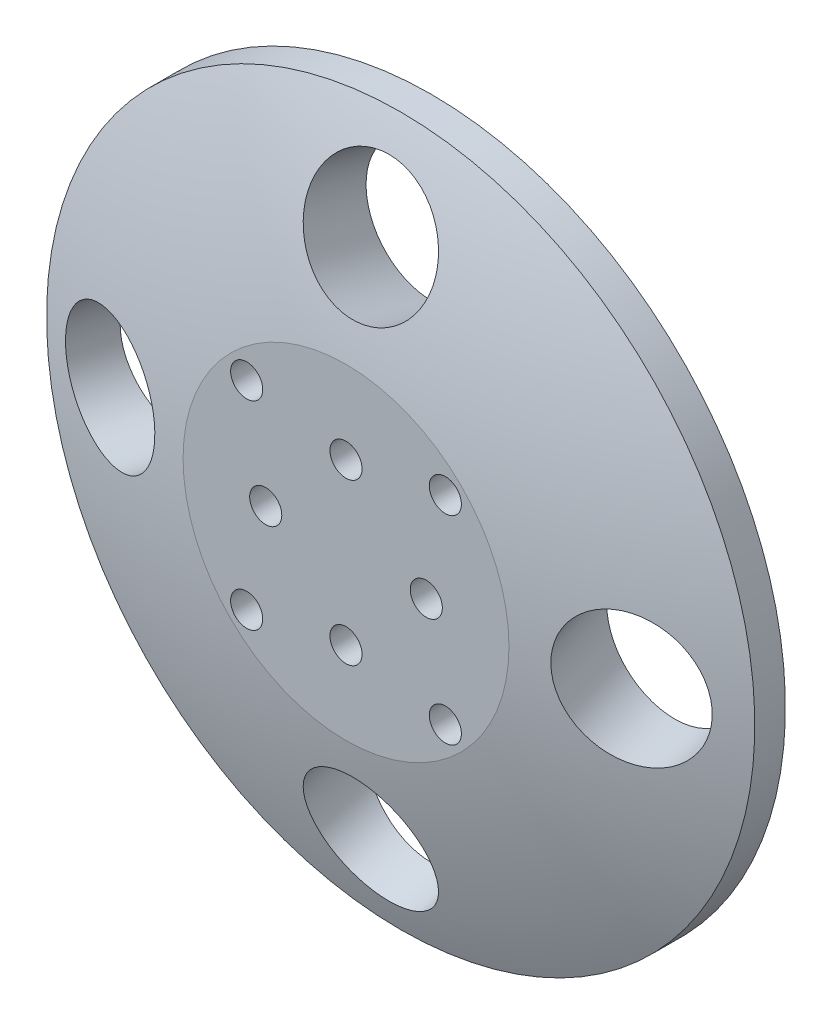
SolidWorks part; units mm, degrees
ref_plane "前视基准面" through (0, 0, 0) normal (0, 0, 1) x (1, 0, 0)
ref_plane "上视基准面" through (0, 0, 0) normal (0, 1, 0) x (1, 0, 0)
ref_plane "右视基准面" through (0, 0, 0) normal (1, 0, 0) x (0, 0, -1)
sketch "草图1" plane through (0, 0, 0) normal (1, 0, 0) x (0, 0, -1)
  line L0 (35.2879, -15.7101) -> (0, -15.7101)
  line L2 (0, 31.2769) -> (0, -237.0192) construction
  line L3 (0, -7.2101) -> (0, -15.7101)
  line L9 (35.2879, -12.6593) -> (35.2879, -15.7101)
  line L10 (16.238, -7.2101) -> (0, -7.2101)
  arc A2 (35.2879, -12.6593) -> (16.238, -7.2101) centre (0, -100) ccw
  dimension "D2" = 8.5
  dimension "D3" = 35.2879
revolve "旋转1" add sketch "草图1" angle 360 about L2
sketch "草图2" plane through (0, 0, 0) normal (1, 0, 0) x (0, 0, -1)
  line L0 (0, 85.1233) -> (0, -119.0001) construction
  line L1 (0.0749, -100.0215) -> (43.0791, 49.9519) construction
  line L2 (30.0594, 4.5467) -> (36.3076, 2.7551)
  line L3 (36.3076, 2.7551) -> (21.5021, -48.8778)
  line L4 (21.5021, -48.8778) -> (15.2539, -47.0861)
  line L7 (30.0594, 4.5467) -> (15.2539, -47.0861)
  dimension "D1" = 16
  dimension "D2" = 6.5
revolve "切除-旋转1" cut sketch "草图2" angle 360 about L1
pattern_circular "阵列(圆周)1" count 4 over 360 about axis through (0, -7.2101, 0) along (0, 1, 0) of "切除-旋转1"
sketch "草图3" plane through (0, -15.7101, 0) normal (0, -1, 0) x (1, 0, 0)
  line L0 (0, 0) -> (9.8995, -9.8995) construction
  line L1 (14, 0) -> (0, 0) construction
  circle A0 centre (0, 0) radius 8 construction
  circle A1 centre (8, 0) radius 1.6
  circle A2 centre (0, 8) radius 1.6
  circle A3 centre (0, -8) radius 1.6
  circle A4 centre (-8, 0) radius 1.6
  circle A5 centre (0, 0) radius 14 construction
  circle A7 centre (9.8995, -9.8995) radius 1.6
  circle A10 centre (-9.8995, -9.8995) radius 1.6
  circle A11 centre (-9.8995, 9.8995) radius 1.6
  circle A12 centre (9.8995, 9.8995) radius 1.6
  point P24 (0, 0)
  dimension "D1" = 45
  dimension "D2" = 4
extrude "切除-拉伸1" cut sketch "草图3" against normal blind 10
move or copy body "实体-移动/复制4" bodies to move or copy 109 copy no rotation origin (0, -11.4601, 0) rotation axis (1, 0, 0) rotation angle 90
